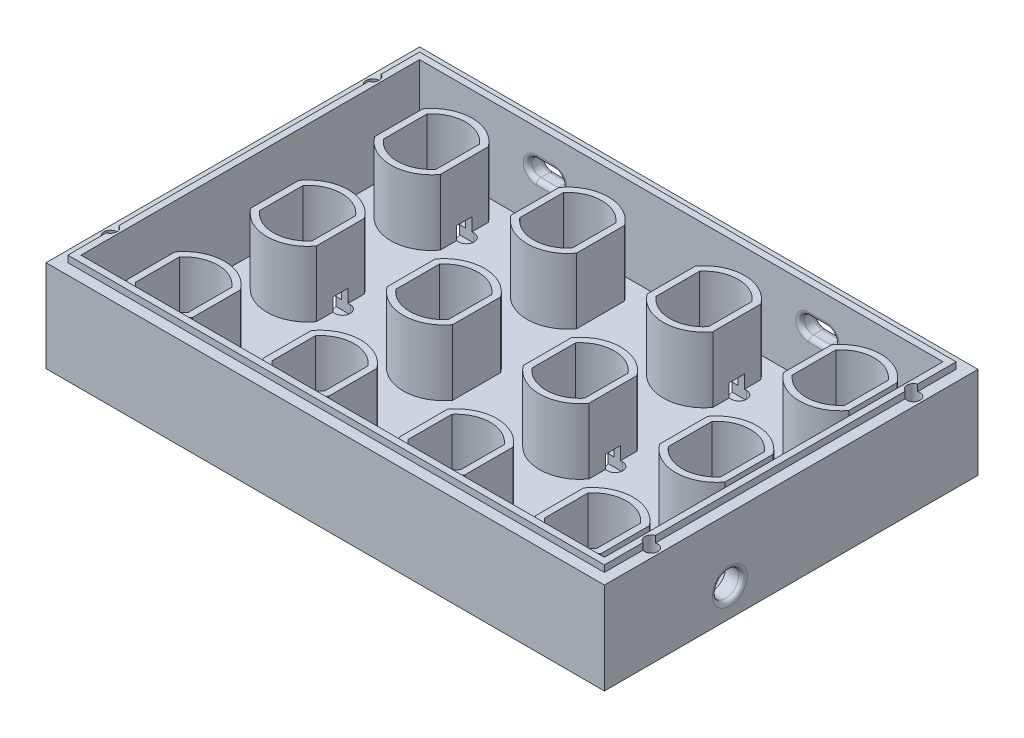
SolidWorks part; units mm, degrees
ref_plane "Front Plane" through (0, 0, 0) normal (0, 0, 1) x (1, 0, 0)
ref_plane "Top Plane" through (0, 0, 0) normal (0, 1, 0) x (1, 0, 0)
ref_plane "Right Plane" through (0, 0, 0) normal (1, 0, 0) x (0, 0, -1)
sketch "Sketch1" plane through (0, 0, 0) normal (0, 1, 0) x (1, 0, 0)
  line L0 (11.122, -9.411) -> (11.122, -19.379)
  line L1 (0, 0) -> (127.76, 0)
  line L2 (0, 0) -> (0, -85.48)
  line L3 (0, -85.48) -> (127.76, -85.48)
  line L4 (127.76, 0) -> (127.76, -85.48)
  line L5 (23.122, -9.411) -> (23.122, -19.379)
  line L6 (42.294, -9.411) -> (42.294, -19.379)
  line L7 (54.294, -9.411) -> (54.294, -19.379)
  line L8 (73.466, -9.411) -> (73.466, -19.379)
  line L9 (85.466, -9.411) -> (85.466, -19.379)
  line L10 (104.638, -9.411) -> (104.638, -19.379)
  line L11 (116.638, -9.411) -> (116.638, -19.379)
  line L12 (42.294, -37.756) -> (42.294, -47.724)
  line L13 (54.294, -37.756) -> (54.294, -47.724)
  line L14 (73.466, -37.756) -> (73.466, -47.724)
  line L15 (85.466, -37.756) -> (85.466, -47.724)
  line L16 (104.638, -37.756) -> (104.638, -47.724)
  line L17 (116.638, -37.756) -> (116.638, -47.724)
  line L18 (42.294, -66.101) -> (42.294, -76.069)
  line L19 (54.294, -66.101) -> (54.294, -76.069)
  line L20 (73.466, -66.101) -> (73.466, -76.069)
  line L21 (85.466, -66.101) -> (85.466, -76.069)
  line L22 (104.638, -66.101) -> (104.638, -76.069)
  line L23 (116.638, -66.101) -> (116.638, -76.069)
  line L24 (11.122, -37.756) -> (11.122, -47.724)
  line L25 (23.122, -37.756) -> (23.122, -47.724)
  line L26 (11.122, -66.101) -> (11.122, -76.069)
  line L27 (23.122, -66.101) -> (23.122, -76.069)
  circle A2 centre (17.122, -14.395) radius 14.05
  circle A12 centre (48.294, -14.395) radius 14.05
  circle A13 centre (79.466, -14.395) radius 14.05
  circle A14 centre (110.638, -14.395) radius 14.05
  circle A15 centre (48.294, -42.74) radius 14.05
  circle A16 centre (79.466, -42.74) radius 14.05
  circle A17 centre (110.638, -42.74) radius 14.05
  circle A18 centre (48.294, -71.085) radius 14.05
  circle A19 centre (79.466, -71.085) radius 14.05
  circle A20 centre (110.638, -71.085) radius 14.05
  circle A21 centre (17.122, -42.74) radius 14.05
  circle A22 centre (17.122, -71.085) radius 14.05
  arc A23 (11.122, -19.379) -> (23.122, -19.379) centre (17.122, -14.395) ccw
  arc A24 (23.122, -9.411) -> (11.122, -9.411) centre (17.122, -14.395) ccw
  arc A25 (42.294, -19.379) -> (54.294, -19.379) centre (48.294, -14.395) ccw
  arc A26 (54.294, -9.411) -> (42.294, -9.411) centre (48.294, -14.395) ccw
  arc A27 (73.466, -19.379) -> (85.466, -19.379) centre (79.466, -14.395) ccw
  arc A28 (85.466, -9.411) -> (73.466, -9.411) centre (79.466, -14.395) ccw
  arc A29 (104.638, -19.379) -> (116.638, -19.379) centre (110.638, -14.395) ccw
  arc A30 (116.638, -9.411) -> (104.638, -9.411) centre (110.638, -14.395) ccw
  arc A31 (42.294, -47.724) -> (54.294, -47.724) centre (48.294, -42.74) ccw
  arc A32 (54.294, -37.756) -> (42.294, -37.756) centre (48.294, -42.74) ccw
  arc A33 (73.466, -47.724) -> (85.466, -47.724) centre (79.466, -42.74) ccw
  arc A34 (85.466, -37.756) -> (73.466, -37.756) centre (79.466, -42.74) ccw
  arc A35 (104.638, -47.724) -> (116.638, -47.724) centre (110.638, -42.74) ccw
  arc A36 (116.638, -37.756) -> (104.638, -37.756) centre (110.638, -42.74) ccw
  arc A37 (42.294, -76.069) -> (54.294, -76.069) centre (48.294, -71.085) ccw
  arc A38 (54.294, -66.101) -> (42.294, -66.101) centre (48.294, -71.085) ccw
  arc A39 (73.466, -76.069) -> (85.466, -76.069) centre (79.466, -71.085) ccw
  arc A40 (85.466, -66.101) -> (73.466, -66.101) centre (79.466, -71.085) ccw
  arc A41 (104.638, -76.069) -> (116.638, -76.069) centre (110.638, -71.085) ccw
  arc A42 (116.638, -66.101) -> (104.638, -66.101) centre (110.638, -71.085) ccw
  arc A43 (11.122, -47.724) -> (23.122, -47.724) centre (17.122, -42.74) ccw
  arc A44 (23.122, -37.756) -> (11.122, -37.756) centre (17.122, -42.74) ccw
  arc A45 (11.122, -76.069) -> (23.122, -76.069) centre (17.122, -71.085) ccw
  arc A46 (23.122, -66.101) -> (11.122, -66.101) centre (17.122, -71.085) ccw
  dimension "D3" = 4
  dimension "D4" = 14.395
  dimension "D9" = 15.6
  dimension "D11" = 28.1
  dimension "D1" = 127.76
  dimension "D2" = 85.48
  dimension "D5" = 3
  dimension "D6" = 14.395
  dimension "D7" = 17.122
  dimension "D8" = 17.122
  dimension "D10" = 12
  dimension "D12" = 4
  dimension "D13" = 3
sketch "Sketch4" plane through (0, 0, 0) normal (0, 1, 0) x (1, 0, 0)
  line L0 (11.122, -9.411) -> (11.122, -19.379)
  line L1 (0, 0) -> (127.76, 0)
  line L2 (0, 0) -> (0, -85.48)
  line L3 (0, -85.48) -> (127.76, -85.48)
  line L4 (127.76, 0) -> (127.76, -85.48)
  line L5 (23.122, -9.411) -> (23.122, -19.379)
  line L6 (42.294, -9.411) -> (42.294, -19.379)
  line L7 (54.294, -9.411) -> (54.294, -19.379)
  line L8 (73.466, -9.411) -> (73.466, -19.379)
  line L9 (85.466, -9.411) -> (85.466, -19.379)
  line L10 (104.638, -9.411) -> (104.638, -19.379)
  line L11 (116.638, -9.411) -> (116.638, -19.379)
  line L12 (42.294, -37.756) -> (42.294, -47.724)
  line L13 (54.294, -37.756) -> (54.294, -47.724)
  line L14 (73.466, -37.756) -> (73.466, -47.724)
  line L15 (85.466, -37.756) -> (85.466, -47.724)
  line L16 (104.638, -37.756) -> (104.638, -47.724)
  line L17 (116.638, -37.756) -> (116.638, -47.724)
  line L18 (42.294, -66.101) -> (42.294, -76.069)
  line L19 (54.294, -66.101) -> (54.294, -76.069)
  line L20 (73.466, -66.101) -> (73.466, -76.069)
  line L21 (85.466, -66.101) -> (85.466, -76.069)
  line L22 (104.638, -66.101) -> (104.638, -76.069)
  line L23 (116.638, -66.101) -> (116.638, -76.069)
  line L24 (11.122, -37.756) -> (11.122, -47.724)
  line L25 (23.122, -37.756) -> (23.122, -47.724)
  line L26 (11.122, -66.101) -> (11.122, -76.069)
  line L27 (23.122, -66.101) -> (23.122, -76.069)
  line L28 (9.622, -8.8959) -> (9.622, -19.8941)
  line L29 (24.622, -8.8959) -> (24.622, -19.8941)
  line L30 (40.794, -8.8959) -> (40.794, -19.8941)
  line L31 (55.794, -8.8959) -> (55.794, -19.8941)
  line L32 (71.966, -8.8959) -> (71.966, -19.8941)
  line L33 (86.966, -8.8959) -> (86.966, -19.8941)
  line L34 (9.622, -37.2409) -> (9.622, -48.2391)
  line L35 (24.622, -37.2409) -> (24.622, -48.2391)
  line L36 (40.794, -37.2409) -> (40.794, -48.2391)
  line L37 (55.794, -37.2409) -> (55.794, -48.2391)
  line L38 (9.622, -65.5859) -> (9.622, -76.5841)
  line L39 (24.622, -65.5859) -> (24.622, -76.5841)
  line L40 (40.794, -65.5859) -> (40.794, -76.5841)
  line L41 (55.794, -65.5859) -> (55.794, -76.5841)
  line L42 (71.966, -65.5859) -> (71.966, -76.5841)
  line L43 (86.966, -65.5859) -> (86.966, -76.5841)
  line L44 (71.966, -37.2409) -> (71.966, -48.2391)
  line L45 (86.966, -37.2409) -> (86.966, -48.2391)
  line L46 (103.138, -8.8959) -> (103.138, -19.8941)
  line L47 (118.138, -8.8959) -> (118.138, -19.8941)
  line L48 (103.138, -37.2409) -> (103.138, -48.2391)
  line L49 (118.138, -37.2409) -> (118.138, -48.2391)
  line L50 (103.138, -65.5859) -> (103.138, -76.5841)
  line L51 (118.138, -65.5859) -> (118.138, -76.5841)
  circle A2 centre (17.122, -14.395) radius 14.05
  circle A12 centre (48.294, -14.395) radius 14.05
  circle A13 centre (79.466, -14.395) radius 14.05
  circle A14 centre (110.638, -14.395) radius 14.05
  circle A15 centre (48.294, -42.74) radius 14.05
  circle A16 centre (79.466, -42.74) radius 14.05
  circle A17 centre (110.638, -42.74) radius 14.05
  circle A18 centre (48.294, -71.085) radius 14.05
  circle A19 centre (79.466, -71.085) radius 14.05
  circle A20 centre (110.638, -71.085) radius 14.05
  circle A21 centre (17.122, -42.74) radius 14.05
  circle A22 centre (17.122, -71.085) radius 14.05
  arc A23 (11.122, -19.379) -> (23.122, -19.379) centre (17.122, -14.395) ccw
  arc A24 (23.122, -9.411) -> (11.122, -9.411) centre (17.122, -14.395) ccw
  arc A25 (42.294, -19.379) -> (54.294, -19.379) centre (48.294, -14.395) ccw
  arc A26 (54.294, -9.411) -> (42.294, -9.411) centre (48.294, -14.395) ccw
  arc A27 (73.466, -19.379) -> (85.466, -19.379) centre (79.466, -14.395) ccw
  arc A28 (85.466, -9.411) -> (73.466, -9.411) centre (79.466, -14.395) ccw
  arc A29 (104.638, -19.379) -> (116.638, -19.379) centre (110.638, -14.395) ccw
  arc A30 (116.638, -9.411) -> (104.638, -9.411) centre (110.638, -14.395) ccw
  arc A31 (42.294, -47.724) -> (54.294, -47.724) centre (48.294, -42.74) ccw
  arc A32 (54.294, -37.756) -> (42.294, -37.756) centre (48.294, -42.74) ccw
  arc A33 (73.466, -47.724) -> (85.466, -47.724) centre (79.466, -42.74) ccw
  arc A34 (85.466, -37.756) -> (73.466, -37.756) centre (79.466, -42.74) ccw
  arc A35 (104.638, -47.724) -> (116.638, -47.724) centre (110.638, -42.74) ccw
  arc A36 (116.638, -37.756) -> (104.638, -37.756) centre (110.638, -42.74) ccw
  arc A37 (42.294, -76.069) -> (54.294, -76.069) centre (48.294, -71.085) ccw
  arc A38 (54.294, -66.101) -> (42.294, -66.101) centre (48.294, -71.085) ccw
  arc A39 (73.466, -76.069) -> (85.466, -76.069) centre (79.466, -71.085) ccw
  arc A40 (85.466, -66.101) -> (73.466, -66.101) centre (79.466, -71.085) ccw
  arc A41 (104.638, -76.069) -> (116.638, -76.069) centre (110.638, -71.085) ccw
  arc A42 (116.638, -66.101) -> (104.638, -66.101) centre (110.638, -71.085) ccw
  arc A43 (11.122, -47.724) -> (23.122, -47.724) centre (17.122, -42.74) ccw
  arc A44 (23.122, -37.756) -> (11.122, -37.756) centre (17.122, -42.74) ccw
  arc A45 (11.122, -76.069) -> (23.122, -76.069) centre (17.122, -71.085) ccw
  arc A46 (23.122, -66.101) -> (11.122, -66.101) centre (17.122, -71.085) ccw
  arc A47 (9.622, -19.8941) -> (24.622, -19.8941) centre (17.122, -14.395) ccw
  arc A48 (24.622, -8.8959) -> (9.622, -8.8959) centre (17.122, -14.395) ccw
  arc A49 (40.794, -19.8941) -> (55.794, -19.8941) centre (48.294, -14.395) ccw
  arc A50 (55.794, -8.8959) -> (40.794, -8.8959) centre (48.294, -14.395) ccw
  arc A51 (71.966, -19.8941) -> (86.966, -19.8941) centre (79.466, -14.395) ccw
  arc A52 (86.966, -8.8959) -> (71.966, -8.8959) centre (79.466, -14.395) ccw
  arc A53 (9.622, -48.2391) -> (24.622, -48.2391) centre (17.122, -42.74) ccw
  arc A54 (24.622, -37.2409) -> (9.622, -37.2409) centre (17.122, -42.74) ccw
  arc A55 (40.794, -48.2391) -> (55.794, -48.2391) centre (48.294, -42.74) ccw
  arc A56 (55.794, -37.2409) -> (40.794, -37.2409) centre (48.294, -42.74) ccw
  arc A57 (9.622, -76.5841) -> (24.622, -76.5841) centre (17.122, -71.085) ccw
  arc A58 (24.622, -65.5859) -> (9.622, -65.5859) centre (17.122, -71.085) ccw
  arc A59 (40.794, -76.5841) -> (55.794, -76.5841) centre (48.294, -71.085) ccw
  arc A60 (55.794, -65.5859) -> (40.794, -65.5859) centre (48.294, -71.085) ccw
  arc A61 (71.966, -76.5841) -> (86.966, -76.5841) centre (79.466, -71.085) ccw
  arc A62 (86.966, -65.5859) -> (71.966, -65.5859) centre (79.466, -71.085) ccw
  arc A63 (71.966, -48.2391) -> (86.966, -48.2391) centre (79.466, -42.74) ccw
  arc A64 (86.966, -37.2409) -> (71.966, -37.2409) centre (79.466, -42.74) ccw
  arc A65 (103.138, -19.8941) -> (118.138, -19.8941) centre (110.638, -14.395) ccw
  arc A66 (118.138, -8.8959) -> (103.138, -8.8959) centre (110.638, -14.395) ccw
  arc A67 (103.138, -48.2391) -> (118.138, -48.2391) centre (110.638, -42.74) ccw
  arc A68 (118.138, -37.2409) -> (103.138, -37.2409) centre (110.638, -42.74) ccw
  arc A69 (103.138, -76.5841) -> (118.138, -76.5841) centre (110.638, -71.085) ccw
  arc A70 (118.138, -65.5859) -> (103.138, -65.5859) centre (110.638, -71.085) ccw
  dimension "D3" = 4
  dimension "D4" = 14.395
  dimension "D9" = 15.6
  dimension "D11" = 28.1
  dimension "D1" = 127.76
  dimension "D2" = 85.48
  dimension "D5" = 3
  dimension "D6" = 14.395
  dimension "D7" = 17.122
  dimension "D8" = 17.122
  dimension "D10" = 12
  dimension "D14" = 1.5
  dimension "D12" = 4
  dimension "D13" = 3
extrude "Boss-Extrude1" add sketch "Sketch4" along normal blind 15 contours L35 A54 L34 A53 A44 L25 A43 L24 | L29 A48 L28 A47 A24 L5 A23 L0 | L31 A50 L30 A49 A26 L7 A25 L6 | L33 A52 L32 A51 A28 L9 A27 L8 | L47 A66 L46 A65 A30 L11 A29 L10 | L49 A68 L48 A67 A36 L17 A35 L16 | L45 A64 L44 A63 A34 L15 A33 L14 | L43 A62 L42 A61 A40 L21 A39 L20 | L51 A70 L50 A69 A42 L23 A41 L22 | L41 A60 L40 A59 A38 L19 A37 L18 | L39 A58 L38 A57 A46 L27 A45 L26 | L37 A56 L36 A55 A32 L13 A31 L12
sketch "Sketch5" plane through (0, 0, 0) normal (0, 1, 0) x (1, 0, 0)
  line L0 (4, -4) -> (4, -81.48)
  line L1 (0, 0) -> (127.76, 0)
  line L2 (0, 0) -> (0, -85.48)
  line L3 (0, -85.48) -> (127.76, -85.48)
  line L4 (127.76, 0) -> (127.76, -85.48)
  line L5 (4, -81.48) -> (123.76, -81.48)
  line L6 (123.76, -4) -> (123.76, -81.48)
  line L7 (4, -4) -> (123.76, -4)
  dimension "D1" = 4
extrude "Boss-Extrude2" add sketch "Sketch5" along normal blind 18 separate body
sketch "Sketch6" plane through (0, 0, 0) normal (0, -1, 0) x (1, 0, 0)
  line L1 (0, 85.48) -> (127.76, 85.48)
  line L2 (0, 85.48) -> (0, 0)
  line L3 (0, 0) -> (127.76, 0)
  line L4 (127.76, 85.48) -> (127.76, 0)
  circle A0 centre (17.122, 71.085) radius 5
  circle A1 centre (48.294, 71.085) radius 5
  circle A2 centre (79.466, 71.085) radius 5
  circle A3 centre (110.638, 71.085) radius 5
  circle A4 centre (48.294, 42.74) radius 5
  circle A5 centre (79.466, 42.74) radius 5
  circle A6 centre (110.638, 42.74) radius 5
  circle A7 centre (48.294, 14.395) radius 5
  circle A8 centre (79.466, 14.395) radius 5
  circle A9 centre (110.638, 14.395) radius 5
  circle A10 centre (17.122, 42.74) radius 5
  circle A11 centre (17.122, 14.395) radius 5
  dimension "D3" = 10
  dimension "D1" = 4
  dimension "D2" = 3
extrude "Boss-Extrude3" add sketch "Sketch6" along normal blind 3
sketch "Sketch8" plane through (0, 0, 0) normal (0, 1, 0) x (1, 0, 0)
  line L0 (127.76, 0) -> (0, 0) construction
  line L1 (2.572, 0) -> (31.672, 0)
  line L2 (2.572, 0) -> (2.572, -85.48)
  line L3 (2.572, -85.48) -> (31.672, -85.48)
  line L4 (31.672, 0) -> (31.672, -85.48)
  line L5 (0, -85.48) -> (127.76, -85.48) construction
  point P8 (17.122, -85.48)
  dimension "D1" = 29.1
sketch "Sketch10" plane through (0, 18, 0) normal (0, 1, 0) x (1, 0, 0)
  line L9 (4, -4) -> (123.76, -4)
  line L10 (4, -4) -> (4, -81.48)
  line L11 (4, -81.48) -> (123.76, -81.48)
  line L12 (125.26, -82.98) -> (125.26, -2.5)
  line L13 (2.5, -82.98) -> (125.26, -82.98)
  line L14 (2.5, -2.5) -> (2.5, -82.98)
  line L15 (125.26, -2.5) -> (2.5, -2.5)
  line L16 (125.26, -82.98) -> (125.26, -2.5)
  line L17 (2.5, -82.98) -> (125.26, -82.98)
  line L18 (2.5, -2.5) -> (2.5, -82.98)
  line L19 (125.26, -2.5) -> (2.5, -2.5)
  line L20 (123.76, -4) -> (123.76, -81.48)
  dimension "D1" = 1.5
extrude "Boss-Extrude4" add sketch "Sketch10" along normal blind 1.5
sketch "Sketch11" plane through (0, 19.5, 0) normal (0, 1, 0) x (1, 0, 0)
  line L3 (127.76, 0) -> (0, 0) construction
  line L4 (0, 0) -> (0, -85.48) construction
  line L5 (127.76, -85.48) -> (127.76, 0) construction
  circle A0 centre (2, -12.74) radius 1.5
  circle A1 centre (2, -72.74) radius 1.5
  circle A2 centre (125.76, -12.74) radius 1.5
  circle A3 centre (125.76, -72.74) radius 1.5
  dimension "D1" = 3
  dimension "D3" = 12.74
  dimension "D4" = 2
  dimension "D2" = 60
  dimension "D5" = 2
extrude "Cut-Extrude1" cut sketch "Sketch11" against normal blind 4.5
sketch "Sketch13" plane through (0, 0, 0) normal (0, 1, 0) x (1, 0, 0)
  line L0 (17.122, -14.395) -> (25.122, -14.395) construction
  line L1 (17.122, -12.645) -> (25.122, -12.645)
  line L2 (17.122, -16.145) -> (25.122, -16.145)
  line L4 (40.294, -14.395) -> (48.294, -14.395) construction
  line L5 (40.294, -12.645) -> (48.294, -12.645)
  line L6 (40.294, -16.145) -> (48.294, -16.145)
  line L7 (40.294, -42.74) -> (48.294, -42.74) construction
  line L8 (40.294, -40.99) -> (48.294, -40.99)
  line L9 (40.294, -44.49) -> (48.294, -44.49)
  line L10 (40.294, -71.085) -> (48.294, -71.085) construction
  line L11 (40.294, -69.335) -> (48.294, -69.335)
  line L12 (40.294, -72.835) -> (48.294, -72.835)
  line L13 (17.122, -42.74) -> (25.122, -42.74) construction
  line L14 (17.122, -40.99) -> (25.122, -40.99)
  line L15 (17.122, -44.49) -> (25.122, -44.49)
  line L16 (17.122, -71.085) -> (25.122, -71.085) construction
  line L17 (17.122, -69.335) -> (25.122, -69.335)
  line L18 (17.122, -72.835) -> (25.122, -72.835)
  line L19 (17.122, -14.395) -> (40.294, -14.395) construction
  line L20 (17.122, -14.395) -> (17.122, -42.74) construction
  line L21 (79.466, -14.395) -> (102.638, -14.395) construction
  line L22 (79.466, -14.395) -> (79.466, -42.74) construction
  line L23 (79.466, -14.395) -> (87.466, -14.395) construction
  line L24 (79.466, -12.645) -> (87.466, -12.645)
  line L25 (79.466, -16.145) -> (87.466, -16.145)
  line L26 (102.638, -14.395) -> (110.638, -14.395) construction
  line L27 (102.638, -12.645) -> (110.638, -12.645)
  line L28 (102.638, -16.145) -> (110.638, -16.145)
  line L29 (102.638, -42.74) -> (110.638, -42.74) construction
  line L30 (102.638, -40.99) -> (110.638, -40.99)
  line L31 (102.638, -44.49) -> (110.638, -44.49)
  line L32 (102.638, -71.085) -> (110.638, -71.085) construction
  line L33 (102.638, -69.335) -> (110.638, -69.335)
  line L34 (102.638, -72.835) -> (110.638, -72.835)
  line L35 (79.466, -42.74) -> (87.466, -42.74) construction
  line L36 (79.466, -40.99) -> (87.466, -40.99)
  line L37 (79.466, -44.49) -> (87.466, -44.49)
  line L38 (79.466, -71.085) -> (87.466, -71.085) construction
  line L39 (79.466, -69.335) -> (87.466, -69.335)
  line L40 (79.466, -72.835) -> (87.466, -72.835)
  line L41 (24.622, -8.8959) -> (24.622, -19.8941) construction
  arc A0 (17.122, -12.645) -> (17.122, -16.145) centre (17.122, -14.395) ccw
  arc A1 (25.122, -16.145) -> (25.122, -12.645) centre (25.122, -14.395) ccw
  arc A2 (40.294, -12.645) -> (40.294, -16.145) centre (40.294, -14.395) ccw
  arc A3 (48.294, -16.145) -> (48.294, -12.645) centre (48.294, -14.395) ccw
  arc A4 (40.294, -40.99) -> (40.294, -44.49) centre (40.294, -42.74) ccw
  arc A5 (48.294, -44.49) -> (48.294, -40.99) centre (48.294, -42.74) ccw
  arc A6 (40.294, -69.335) -> (40.294, -72.835) centre (40.294, -71.085) ccw
  arc A7 (48.294, -72.835) -> (48.294, -69.335) centre (48.294, -71.085) ccw
  arc A8 (17.122, -40.99) -> (17.122, -44.49) centre (17.122, -42.74) ccw
  arc A9 (25.122, -44.49) -> (25.122, -40.99) centre (25.122, -42.74) ccw
  arc A10 (17.122, -69.335) -> (17.122, -72.835) centre (17.122, -71.085) ccw
  arc A11 (25.122, -72.835) -> (25.122, -69.335) centre (25.122, -71.085) ccw
  circle A16 centre (48.294, -71.085) radius 5 construction
  arc A17 (79.466, -12.645) -> (79.466, -16.145) centre (79.466, -14.395) ccw
  arc A18 (87.466, -16.145) -> (87.466, -12.645) centre (87.466, -14.395) ccw
  arc A19 (102.638, -12.645) -> (102.638, -16.145) centre (102.638, -14.395) ccw
  arc A20 (110.638, -16.145) -> (110.638, -12.645) centre (110.638, -14.395) ccw
  arc A21 (102.638, -40.99) -> (102.638, -44.49) centre (102.638, -42.74) ccw
  arc A22 (110.638, -44.49) -> (110.638, -40.99) centre (110.638, -42.74) ccw
  arc A23 (102.638, -69.335) -> (102.638, -72.835) centre (102.638, -71.085) ccw
  arc A24 (110.638, -72.835) -> (110.638, -69.335) centre (110.638, -71.085) ccw
  arc A25 (79.466, -40.99) -> (79.466, -44.49) centre (79.466, -42.74) ccw
  arc A26 (87.466, -44.49) -> (87.466, -40.99) centre (87.466, -42.74) ccw
  arc A27 (79.466, -69.335) -> (79.466, -72.835) centre (79.466, -71.085) ccw
  arc A28 (87.466, -72.835) -> (87.466, -69.335) centre (87.466, -71.085) ccw
  circle A29 centre (79.466, -14.395) radius 5 construction
  point P3 (21.122, -14.395)
  point P15 (44.294, -14.395)
  point P22 (44.294, -42.74)
  point P29 (44.294, -71.085)
  point P36 (21.122, -42.74)
  point P43 (21.122, -71.085)
  point P54 (83.466, -14.395)
  point P61 (106.638, -14.395)
  point P68 (106.638, -42.74)
  point P75 (106.638, -71.085)
  point P82 (83.466, -42.74)
  point P89 (83.466, -71.085)
  dimension "D1" = 1.75
  dimension "D4" = 90
  dimension "D6" = 0.5
  dimension "D2" = 2
  dimension "D3" = 3
  dimension "D5" = 2
extrude "Cut-Extrude3" cut sketch "Sketch13" against normal blind 5 from offset 3
sketch "Sketch14" plane through (0, 0, 0) normal (0, 0, -1) x (-1, 0, 0)
  line L0 (-97.053, 11) -> (-93.053, 11) construction
  line L1 (-97.053, 13) -> (-93.053, 13)
  line L2 (-97.053, 9) -> (-93.053, 9)
  line L3 (-34.709, 11) -> (-30.709, 11) construction
  line L4 (-34.709, 13) -> (-30.709, 13)
  line L5 (-34.709, 9) -> (-30.709, 9)
  line L7 (0, -3) -> (-127.76, -3) construction
  line L8 (-103.138, 15) -> (-103.138, 0) construction
  line L11 (-40.794, 15) -> (-40.794, 0) construction
  arc A0 (-97.053, 13) -> (-97.053, 9) centre (-97.053, 11) ccw
  arc A1 (-93.053, 9) -> (-93.053, 13) centre (-93.053, 11) ccw
  arc A2 (-34.709, 13) -> (-34.709, 9) centre (-34.709, 11) ccw
  arc A3 (-30.709, 9) -> (-30.709, 13) centre (-30.709, 11) ccw
  point P2 (-95.053, 11)
  point P11 (-32.709, 11)
  dimension "D3" = 2
  dimension "D6" = 6.085
  dimension "D2" = 4
  dimension "D4" = 12
  dimension "D5" = 6.085
  dimension "D1" = 2
extrude "Cut-Extrude4" cut sketch "Sketch14" against normal blind 5
fillet "Fillet1" radius 1 16 edges at (36.709, 11, 4) (32.709, 9, 4) (28.709, 11, 4) (99.053, 11, 4) (95.053, 9, 4) (91.053, 11, 4) (28.709, 11, 0) (32.709, 9, 0) (36.709, 11, 0) (91.053, 11, 0) (95.053, 9, 0) (99.053, 11, 0) (32.709, 13, 4) (95.053, 13, 4) (32.709, 13, 0) (95.053, 13, 0)
sketch "Sketch15" plane through (127.76, 0, 0) normal (1, 0, 0) x (0, 0, -1)
  line L0 (-81.48, 0) -> (-4, 0) construction
  line L3 (-61.785, 0) -> (-61.785, 15) construction
  circle A0 centre (-56.785, 3.5) radius 3
  dimension "D1" = 6
  dimension "D2" = 3.5
  dimension "D3" = 5
extrude "Cut-Extrude5" cut sketch "Sketch15" against normal blind 5
fillet "Fillet2" radius 1 1 edges at (127.76, 3.5, 53.785)
